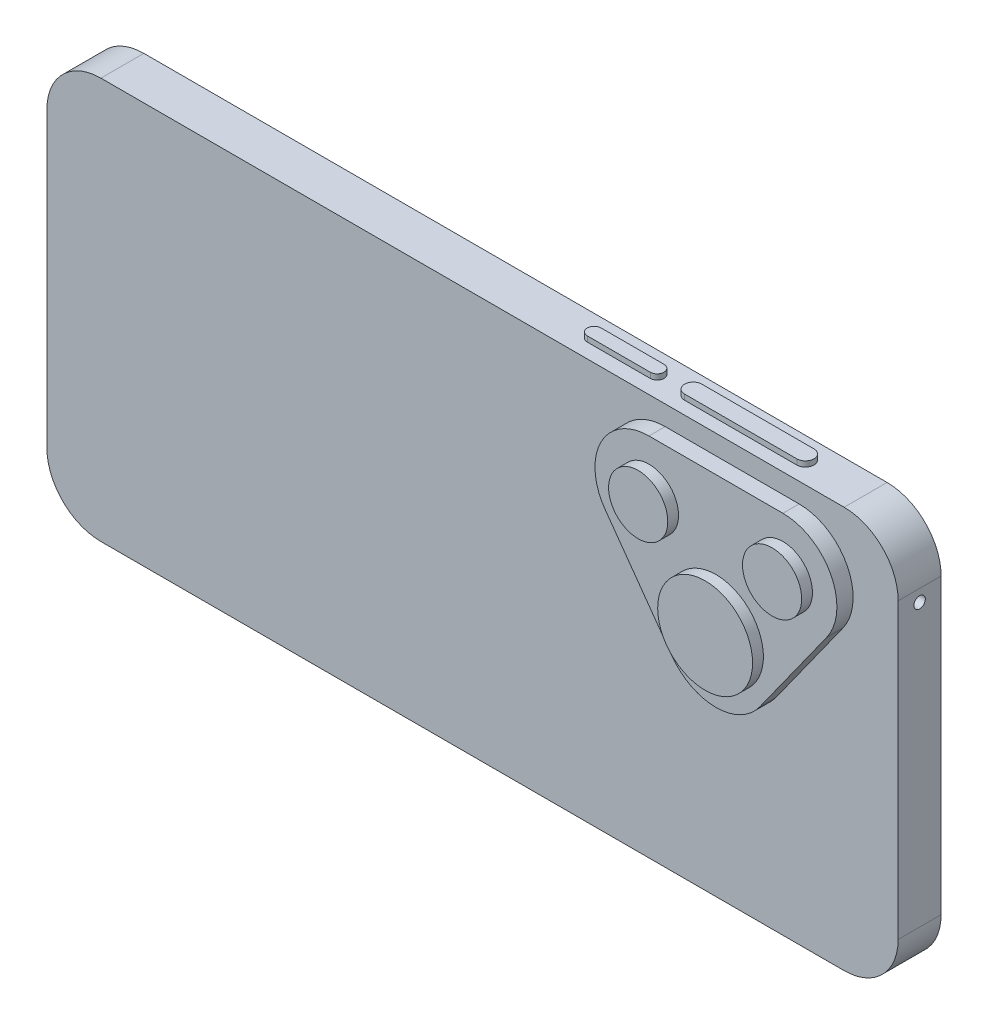
SolidWorks part; units mm, degrees
ref_plane "前视基准面" through (0, 0, 0) normal (0, 0, 1) x (1, 0, 0)
ref_plane "上视基准面" through (0, 0, 0) normal (0, 1, 0) x (1, 0, 0)
ref_plane "右视基准面" through (0, 0, 0) normal (1, 0, 0) x (0, 0, -1)
other "Configuration Table"
sketch "草图1" plane through (0, 0, 0) normal (0, 0, 1) x (1, 0, 0)
  line L1 (-68.8, 37.15) -> (68.8, 37.15)
  line L2 (-78.8, 27.15) -> (-78.8, -27.15)
  line L3 (-68.8, -37.15) -> (68.8, -37.15)
  line L4 (78.8, 27.15) -> (78.8, -27.15)
  line L5 (-78.8, 37.15) -> (78.8, -37.15) construction
  line L6 (-78.8, -37.15) -> (78.8, 37.15) construction
  arc A0 (68.8, -37.15) -> (78.8, -27.15) centre (68.8, -27.15) ccw
  arc A1 (78.8, 27.15) -> (68.8, 37.15) centre (68.8, 27.15) ccw
  arc A2 (-68.8, -37.15) -> (-78.8, -27.15) centre (-68.8, -27.15) cw
  arc A3 (-78.8, 27.15) -> (-68.8, 37.15) centre (-68.8, 27.15) cw
  point P0 (0, 0)
  dimension "D3" = 10
  dimension "D1" = 157.6
  dimension "D2" = 74.3
extrude "凸台-拉伸1" add sketch "草图1" along normal blind 7.95
sketch "草图3" plane through (0, 0, 0) normal (0, 0, -1) x (-1, 0, 0)
  line L8 (-68.8, -36.1) -> (68.8, -36.1)
  line L9 (77.75, -27.15) -> (77.75, 27.15)
  line L10 (68.8, 36.1) -> (-68.8, 36.1)
  line L11 (-77.75, 27.15) -> (-77.75, -27.15)
  line L12 (-68.8, -36.1) -> (68.8, -36.1)
  line L13 (77.75, -27.15) -> (77.75, 27.15)
  line L14 (68.8, 36.1) -> (-68.8, 36.1)
  line L15 (-77.75, 27.15) -> (-77.75, -27.15)
  arc A8 (-77.75, -27.15) -> (-68.8, -36.1) centre (-68.8, -27.15) ccw
  arc A9 (68.8, -36.1) -> (77.75, -27.15) centre (68.8, -27.15) ccw
  arc A10 (77.75, 27.15) -> (68.8, 36.1) centre (68.8, 27.15) ccw
  arc A11 (-68.8, 36.1) -> (-77.75, 27.15) centre (-68.8, 27.15) ccw
  arc A12 (-77.75, -27.15) -> (-68.8, -36.1) centre (-68.8, -27.15) ccw
  arc A13 (68.8, -36.1) -> (77.75, -27.15) centre (68.8, -27.15) ccw
  arc A14 (77.75, 27.15) -> (68.8, 36.1) centre (68.8, 27.15) ccw
  arc A15 (-68.8, 36.1) -> (-77.75, 27.15) centre (-68.8, 27.15) ccw
  dimension "D1" = 1.05
extrude "切除-拉伸11" cut sketch "草图3" against normal blind 0.001 flip side to cut
sketch "草图4" plane through (0, 0, 0) normal (0, 0, -1) x (-1, 0, 0)
  circle A0 centre (-75.1406, 0) radius 1.771
sketch "草图5" plane through (78.8, 0, 0) normal (1, 0, 0) x (0, 0, -1)
  circle A0 centre (-3.9755, 24.9264) radius 1.057
extrude "切除-拉伸12" cut sketch "草图5" against normal blind 5
sketch "草图6" plane through (0, 37.15, 0) normal (0, 1, 0) x (1, 0, 0)
  line L0 (36.8814, -3.9755) -> (57.6537, -3.9755) construction
  line L1 (36.8814, -2.3846) -> (57.6537, -2.3846)
  line L2 (36.8814, -5.5664) -> (57.6537, -5.5664)
  line L3 (30.2046, -3.9755) -> (18.5467, -3.9755) construction
  line L4 (30.2046, -5.2485) -> (18.5467, -5.2485)
  line L5 (30.2046, -2.7025) -> (18.5467, -2.7025)
  arc A0 (36.8814, -2.3846) -> (36.8814, -5.5664) centre (36.8814, -3.9755) ccw
  arc A1 (57.6537, -5.5664) -> (57.6537, -2.3846) centre (57.6537, -3.9755) ccw
  arc A2 (30.2046, -5.2485) -> (30.2046, -2.7025) centre (30.2046, -3.9755) ccw
  arc A3 (18.5467, -2.7025) -> (18.5467, -5.2485) centre (18.5467, -3.9755) ccw
  point P2 (47.2676, -3.9755)
  point P8 (24.3756, -3.9755)
extrude "凸台-拉伸2" add sketch "草图6" along normal blind 1
sketch "草图7" plane through (-78.8, 0, 0) normal (-1, 0, 0) x (0, 0, 1)
  line L0 (3.9755, -3.2195) -> (3.9755, 3.2195) construction
  line L1 (3.211, -3.2195) -> (3.211, 3.2195)
  line L2 (4.74, -3.2195) -> (4.74, 3.2195)
  arc A0 (3.211, -3.2195) -> (4.74, -3.2195) centre (3.9755, -3.2195) ccw
  arc A1 (4.74, 3.2195) -> (3.211, 3.2195) centre (3.9755, 3.2195) ccw
  point P2 (3.9755, 0)
extrude "切除-拉伸13" cut sketch "草图7" against normal blind 5
sketch "草图8" plane through (-78.8, 0, 0) normal (-1, 0, 0) x (0, 0, 1)
  circle A0 centre (3.9755, 25.2376) radius 0.7864
  circle A1 centre (3.9755, 22.6164) radius 0.7864
  circle A2 centre (3.9755, 19.9952) radius 0.7864
  circle A3 centre (3.9755, 17.5706) radius 0.7864
  circle A4 centre (3.9755, 15.146) radius 0.7864
  circle A5 centre (3.9755, 12.5903) radius 0.7864
extrude "切除-拉伸14" cut sketch "草图8" against normal blind 5
sketch "草图9" plane through (-78.8, 0, 0) normal (-1, 0, 0) x (0, 0, 1)
  line L0 (3.9755, -14.8013) -> (3.9755, -25.155) construction
  line L1 (4.7209, -14.8013) -> (4.7209, -25.155)
  line L2 (3.2301, -14.8013) -> (3.2301, -25.155)
  arc A0 (4.7209, -14.8013) -> (3.2301, -14.8013) centre (3.9755, -14.8013) ccw
  arc A1 (3.2301, -25.155) -> (4.7209, -25.155) centre (3.9755, -25.155) ccw
  point P2 (3.9755, -19.9782)
sketch "草图11" plane through (-78.8, 0, 0) normal (-1, 0, 0) x (0, 0, 1)
  circle A0 centre (3.9755, -25.155) radius 0.4587
extrude "切除-拉伸15" cut sketch "草图11" against normal blind 5
sketch "草图13" plane through (0, 0, 7.95) normal (0, 0, 1) x (1, 0, 0)
  line L0 (35.6658, 33.5131) -> (60.459, 33.5131)
  line L1 (68.5917, 17.6943) -> (56.1952, 0.368)
  line L2 (39.9297, 0.368) -> (27.5331, 17.6943)
  arc A0 (56.1952, 0.368) -> (39.9297, 0.368) centre (48.0624, 6.1868) cw
  arc A1 (68.5917, 17.6943) -> (60.459, 33.5131) centre (60.459, 23.5131) ccw
  arc A2 (35.6658, 33.5131) -> (27.5331, 17.6943) centre (35.6658, 23.5131) ccw
  dimension "D1" = 10
extrude "凸台-拉伸3" add sketch "草图13" along normal blind 3
sketch "草图14" plane through (0, 0, 10.95) normal (0, 0, 1) x (1, 0, 0)
  line L0 (44.1941, 27.2602) -> (51.9307, 27.2602) construction
  line L1 (44.1941, 28.32) -> (51.9307, 28.32)
  line L2 (44.1941, 26.2004) -> (51.9307, 26.2004)
  circle A1 centre (48.0624, 8.7135) radius 8.7843
  circle A2 centre (35.6658, 23.5131) radius 5.4777
  circle A3 centre (60.459, 23.5131) radius 5.4777
  arc A4 (44.1941, 28.32) -> (44.1941, 26.2004) centre (44.1941, 27.2602) ccw
  arc A5 (51.9307, 26.2004) -> (51.9307, 28.32) centre (51.9307, 27.2602) ccw
  point P9 (48.0624, 27.2602)
extrude "凸台-拉伸4" add sketch "草图14" along normal blind 2 contours A2 | A3 | A1
sketch "草图15" plane through (0, 0, 12.95) normal (0, 0, 1) x (1, 0, 0)
  circle A0 centre (35.6658, 23.5131) radius 4.6851
  circle A1 centre (60.459, 23.5131) radius 4.6851
  circle A2 centre (48.0624, 8.7135) radius 7.7055
sketch "草图16" plane through (-78.8, 0, 0) normal (-1, 0, 0) x (0, 0, 1)
  circle A0 centre (3.9755, -5.6271) radius 0.4797
